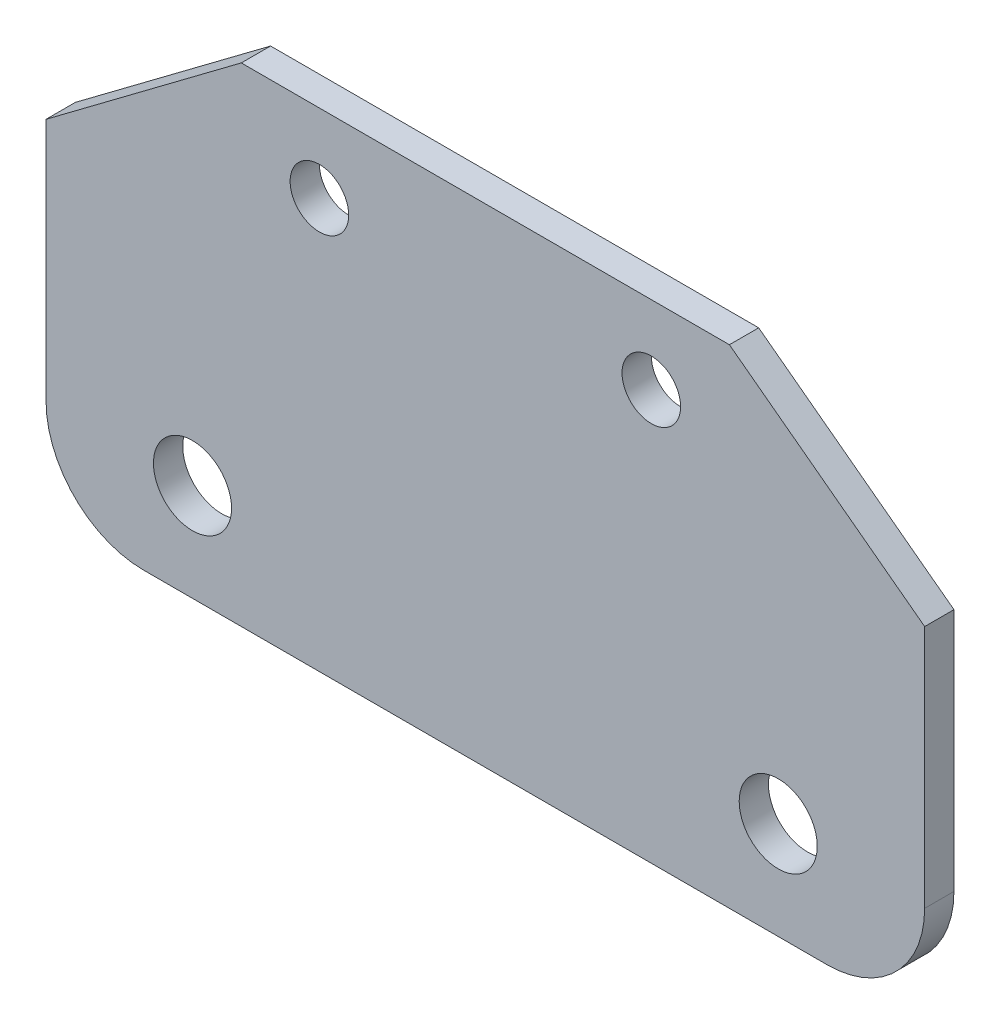
SolidWorks part; units mm, degrees
material "Alumina"
ref_plane "Front Plane" through (0, 0, 0) normal (0, 0, 1) x (1, 0, 0)
ref_plane "Top Plane" through (0, 0, 0) normal (0, 1, 0) x (1, 0, 0)
ref_plane "Right Plane" through (0, 0, 0) normal (1, 0, 0) x (0, 0, -1)
sketch "Sketch1" plane through (0, 0, 0) normal (0, 0, 1) x (1, 0, 0)
  line L0 (0, 35) -> (20, 50)
  line L1 (0, 0) -> (90, 0)
  line L2 (0, 0) -> (0, 35)
  line L3 (20, 50) -> (70, 50)
  line L4 (90, 0) -> (90, 35)
  line L5 (45, 50) -> (45, 0) construction
  line L6 (90, 35) -> (70, 50)
  circle A0 centre (28, 42) radius 3
  circle A1 centre (15, 10) radius 4
  circle A2 centre (75, 10) radius 4
  circle A3 centre (62, 42) radius 3
  dimension "D7" = 6
  dimension "D8" = 8
  dimension "D1" = 20
  dimension "D2" = 35
  dimension "D3" = 32
  dimension "D4" = 90
  dimension "D5" = 15
  dimension "D6" = 13
  dimension "D9" = 15
  dimension "D10" = 10
extrude "Boss-Extrude1" add sketch "Sketch1" along normal blind 3
fillet "Fillet1" radius 10 2 edges at (0, 0, 1.5) (90, 0, 1.5)
